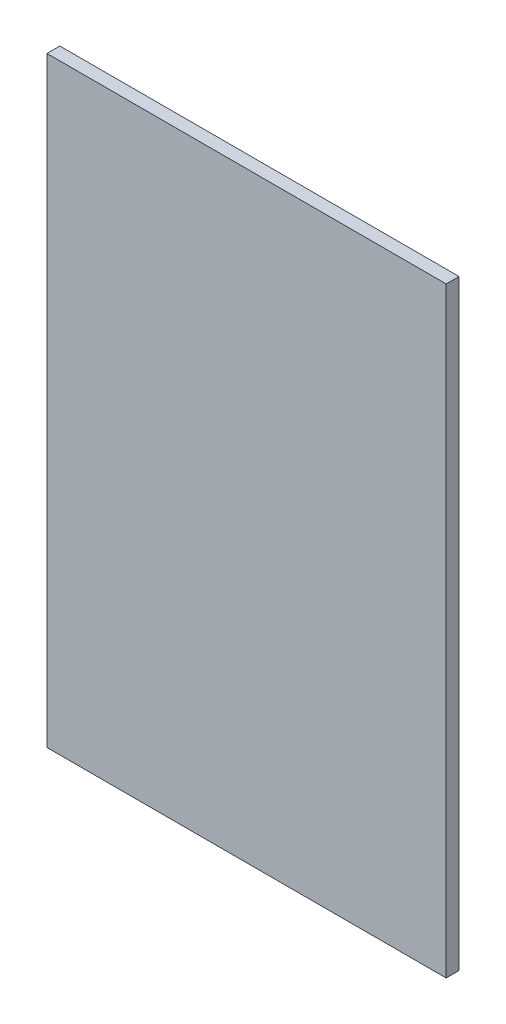
SolidWorks part; units mm, degrees
ref_plane "Front Plane" through (0, 0, 0) normal (0, 0, 1) x (1, 0, 0)
ref_plane "Top Plane" through (0, 0, 0) normal (0, 1, 0) x (1, 0, 0)
ref_plane "Right Plane" through (0, 0, 0) normal (1, 0, 0) x (0, 0, -1)
sketch "Sketch1" plane through (0, 0, 0) normal (0, 0, 1) x (1, 0, 0)
  line L1 (0, 0) -> (123.8, 0)
  line L2 (0, 0) -> (0, -186.4)
  line L3 (0, -186.4) -> (123.8, -186.4)
  line L4 (123.8, 0) -> (123.8, -186.4)
  dimension "D1" = 123.8
  dimension "D2" = 186.4
extrude "Boss-Extrude1" add sketch "Sketch1" along normal blind 4
